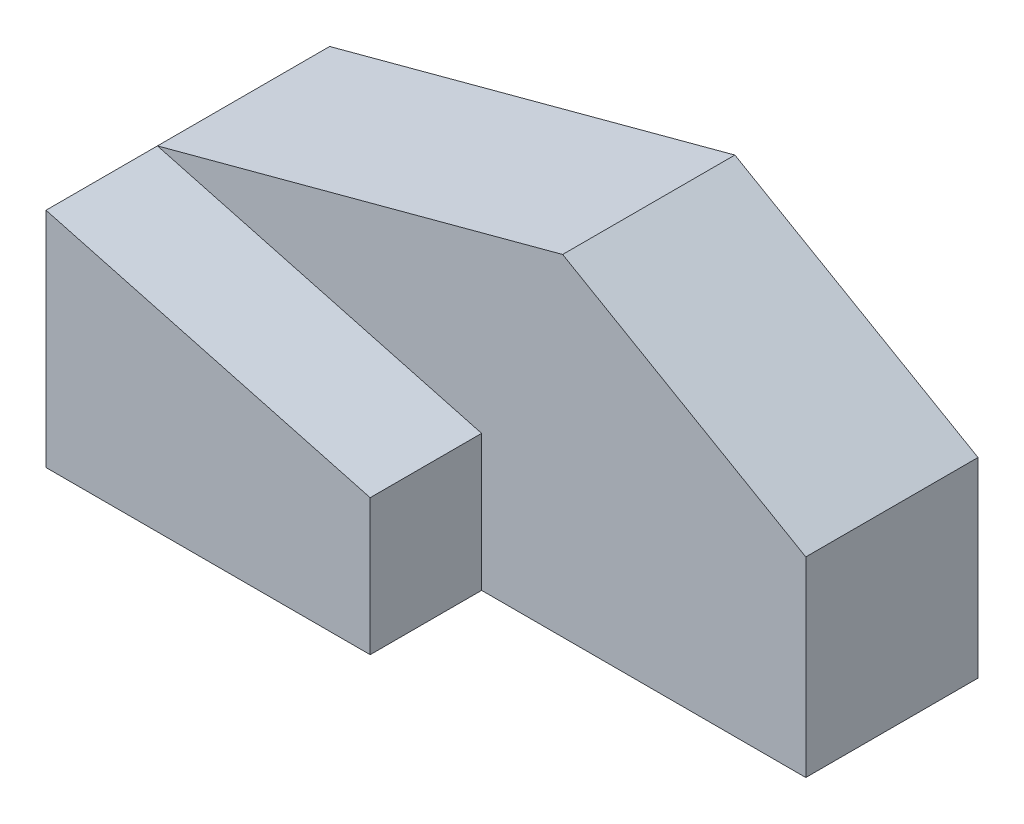
SolidWorks part; units mm, degrees
ref_plane "前基準面" through (0, 0, 0) normal (0, 0, 1) x (1, 0, 0)
ref_plane "上基準面" through (0, 0, 0) normal (0, 1, 0) x (1, 0, 0)
ref_plane "右基準面" through (0, 0, 0) normal (1, 0, 0) x (0, 0, -1)
sketch "草圖3" plane through (0, 0, 0) normal (0, 0, 1) x (1, 0, 0)
  line L0 (0, 0) -> (64, 0)
  line L1 (64, 0) -> (64, 18.8616)
  line L2 (64, 18.8616) -> (40, 32.718)
  line L3 (40, 32.718) -> (0, 22)
  line L4 (0, 22) -> (0, 0)
  dimension "D1" = 135
  dimension "D2" = 40
  dimension "D3" = 22
  dimension "D4" = 105
  dimension "D5" = 64
extrude "填料-伸長3" add sketch "草圖3" against normal blind 17
sketch "草圖4" plane through (0, 0, 0) normal (0, 0, 1) x (1, 0, 0)
  line L0 (0, 0) -> (32, 0)
  line L1 (0, 0) -> (64, 0) construction
  line L2 (32, 0) -> (32, 13.4256)
  line L3 (32, 13.4256) -> (0, 22)
  line L4 (0, 22) -> (0, 0)
  line L5 (40, 32.718) -> (0, 22) construction
  dimension "D1" = 30
  dimension "D2" = 32
extrude "填料-伸長4" add sketch "草圖4" along normal blind 11
